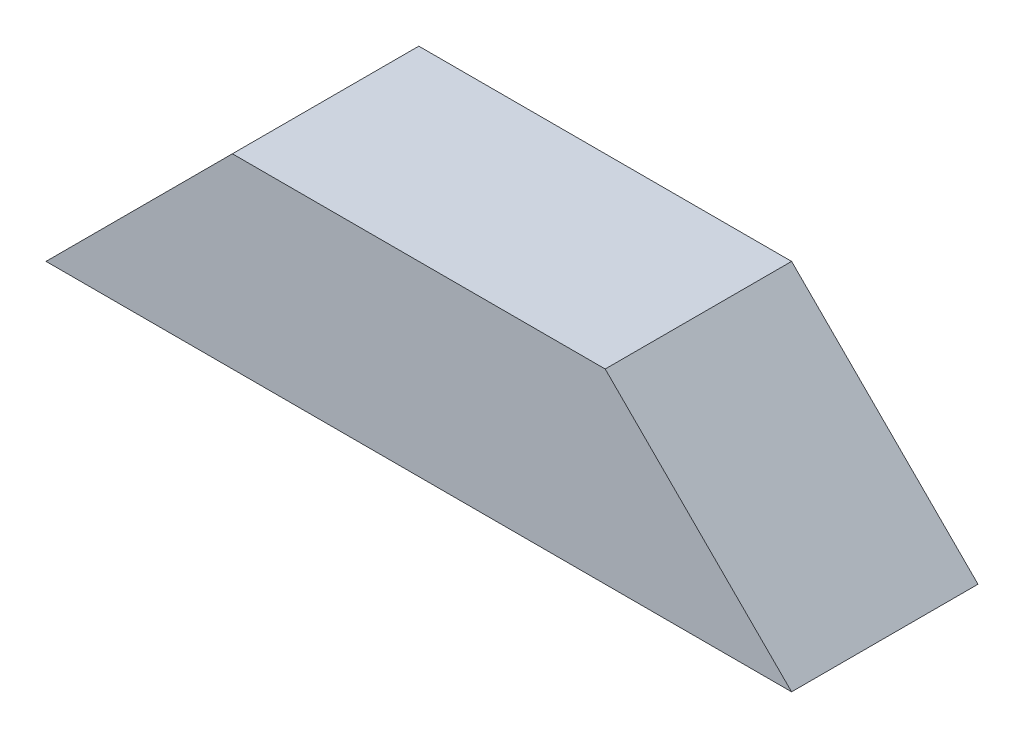
SolidWorks part; units mm, degrees
ref_plane "Plan de face" through (0, 0, 0) normal (0, 0, 1) x (1, 0, 0)
ref_plane "Plan de dessus" through (0, 0, 0) normal (0, 1, 0) x (1, 0, 0)
ref_plane "Plan de droite" through (0, 0, 0) normal (1, 0, 0) x (0, 0, -1)
sketch "Esquisse1" plane through (0, 0, 0) normal (0, 0, 1) x (1, 0, 0)
  line L1 (0, 0) -> (80, 0)
  line L2 (0, 0) -> (0, 20)
  line L3 (0, 20) -> (80, 20)
  line L4 (80, 0) -> (80, 20)
  dimension "D1" = 80
  dimension "D2" = 20
extrude "Boss.-Extru.1" add sketch "Esquisse1" along normal blind 20
sketch "Esquisse2" plane through (0, 0, 20) normal (0, 0, 1) x (1, 0, 0)
  line L0 (40, 0) -> (40, 20) construction
  line L9 (0, 0) -> (80, 0) construction
  line L10 (80, 20) -> (0, 20) construction
  line L11 (0, 20) -> (20, 20)
  line L12 (20, 20) -> (0, 0)
  line L13 (0, 0) -> (0, 20)
  line L14 (80, 0) -> (80, 20)
  line L15 (60, 20) -> (80, 0)
  line L16 (80, 20) -> (60, 20)
  dimension "D1" = 45
extrude "Enlèv. mat.-Extru.1" cut sketch "Esquisse2" against normal through all both and the other way through all
